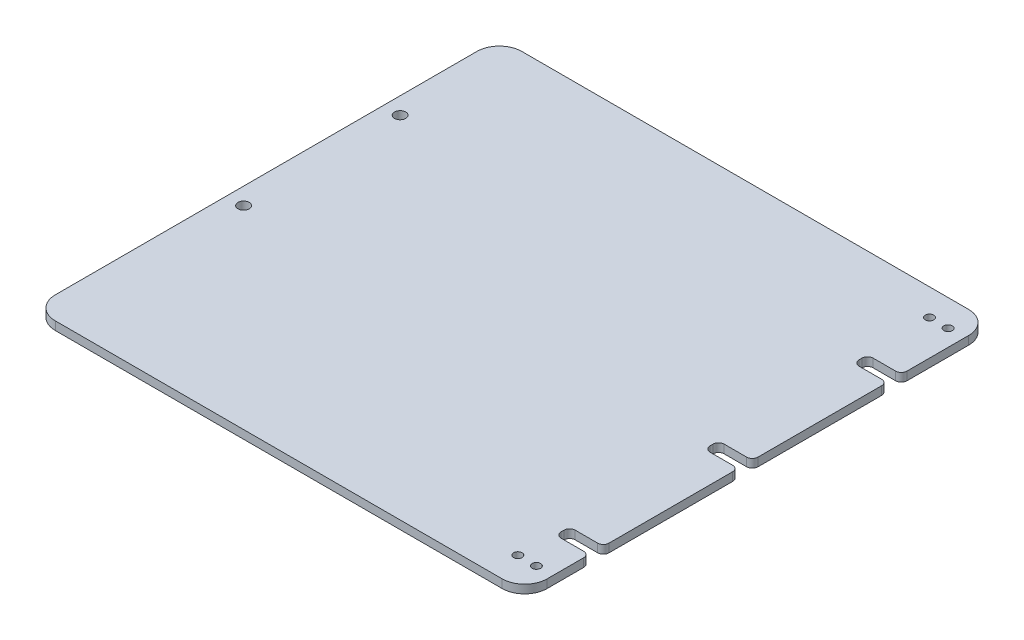
SolidWorks part; units mm, degrees
ref_plane "Front" through (0, 0, 0) normal (0, 0, 1) x (1, 0, 0)
ref_plane "Top" through (0, 0, 0) normal (0, 1, 0) x (1, 0, 0)
ref_plane "Right" through (0, 0, 0) normal (1, 0, 0) x (0, 0, -1)
sketch "草图1" plane through (0, 0, 0) normal (0, 1, 0) x (1, 0, 0)
  line L0 (6, 166) -> (6, 0) construction
  line L1 (0, 0) -> (175, 0)
  line L2 (0, 0) -> (0, 166)
  line L3 (0, 166) -> (175, 166)
  line L4 (175, 0) -> (175, 166)
  circle A0 centre (6, 124.7) radius 2
  circle A1 centre (6, 69) radius 2
  dimension "D3" = 4
  dimension "D4" = 4
  dimension "D1" = 166
  dimension "D2" = 175
  dimension "D5" = 55.7
  dimension "D6" = 69
  dimension "D7" = 12
extrude "凸台-拉伸1" add sketch "草图1" along normal blind 3
sketch "草图2" plane through (0, 3, 0) normal (0, 1, 0) x (1, 0, 0)
  line L0 (175, 0) -> (175, 166) construction
  line L1 (175, 134) -> (163, 134)
  line L2 (175, 134) -> (175, 129)
  line L3 (175, 129) -> (163, 129)
  line L4 (163, 134) -> (163, 129)
  line L5 (175, 166) -> (0, 166) construction
  line L6 (175, 76) -> (163, 76)
  line L7 (163, 81) -> (163, 76)
  line L8 (175, 81) -> (163, 81)
  line L9 (175, 81) -> (175, 76)
  line L10 (175, 23) -> (163, 23)
  line L11 (163, 28) -> (163, 23)
  line L12 (175, 28) -> (163, 28)
  line L13 (175, 28) -> (175, 23)
  dimension "D1" = 5
  dimension "D2" = 12
  dimension "D3" = 32
  dimension "D5" = 48
  dimension "D4" = 3
extrude "切除-拉伸1" cut sketch "草图2" against normal through all
fillet "圆角1" radius 2 12 edges at (163, 1.5, -23) (175, 1.5, -23) (175, 1.5, -28) (163, 1.5, -28) (163, 1.5, -81) (175, 1.5, -81) (175, 1.5, -76) (163, 1.5, -76) (175, 1.5, -134) (175, 1.5, -129) (163, 1.5, -129) (163, 1.5, -134)
sketch "草图3" plane through (0, 3, 0) normal (0, 1, 0) x (1, 0, 0)
  line L0 (40, 141) -> (120, 141) construction
  line L1 (40, 149) -> (120, 149)
  line L2 (40, 133) -> (120, 133)
  line L3 (40, 101) -> (120, 101) construction
  line L4 (40, 109) -> (120, 109)
  line L5 (40, 93) -> (120, 93)
  line L6 (40, 61) -> (120, 61) construction
  line L7 (40, 69) -> (120, 69)
  line L8 (40, 53) -> (120, 53)
  line L9 (0, 166) -> (0, 0) construction
  line L10 (175, 166) -> (0, 166) construction
  line L11 (40, 21) -> (120, 21) construction
  line L12 (40, 29) -> (120, 29)
  line L13 (40, 13) -> (120, 13)
  arc A0 (40, 149) -> (40, 133) centre (40, 141) ccw
  arc A1 (120, 133) -> (120, 149) centre (120, 141) ccw
  arc A2 (40, 109) -> (40, 93) centre (40, 101) ccw
  arc A3 (120, 93) -> (120, 109) centre (120, 101) ccw
  arc A4 (40, 69) -> (40, 53) centre (40, 61) ccw
  arc A5 (120, 53) -> (120, 69) centre (120, 61) ccw
  arc A6 (40, 29) -> (40, 13) centre (40, 21) ccw
  arc A7 (120, 13) -> (120, 29) centre (120, 21) ccw
  point P2 (80, 141)
  point P10 (80, 101)
  point P17 (80, 61)
  point P28 (80, 21)
  dimension "D1" = 8
  dimension "D2" = 80
  dimension "D3" = 40
  dimension "D4" = 25
  dimension "D5" = 4
extrude "切除-拉伸2" [suppressed] cut sketch "草图3" against normal through all
fillet "圆角2" radius 8 4 edges at (0, 1.5, -166) (175, 1.5, -166) (175, 1.5, 0) (0, 1.5, 0)
sketch "草图4" plane through (0, 3, 0) normal (0, 1, 0) x (1, 0, 0)
  circle A0 centre (162.499, 10.0827) radius 1.5
  circle A1 centre (169.1079, 10.0827) radius 1.5
  circle A2 centre (162.499, 156.545) radius 1.5
  circle A3 centre (169.1079, 156.545) radius 1.5
  point P8 (169.1079, 156.545)
  point P9 (160.5595, 156.545)
  point P10 (162.499, 156.545)
  point P11 (169.1079, 10.0827)
  point P12 (162.499, 10.0827)
  dimension "D1" = 3
  dimension "D2" = 3
  dimension "D3" = 3
  dimension "D4" = 3
extrude "切除-拉伸3" cut sketch "草图4" against normal through all
